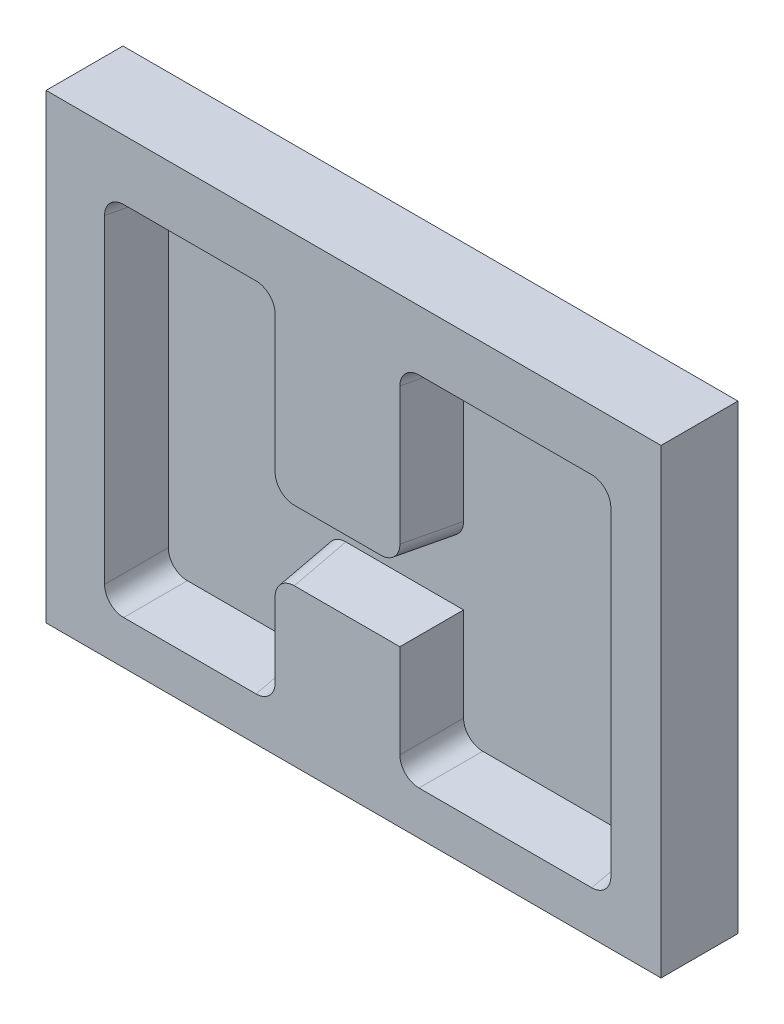
SolidWorks part; units mm, degrees
ref_plane "Front" through (0, 0, 0) normal (0, 0, 1) x (1, 0, 0)
ref_plane "Top" through (0, 0, 0) normal (0, 1, 0) x (1, 0, 0)
ref_plane "Right" through (0, 0, 0) normal (1, 0, 0) x (0, 0, -1)
sketch "Sketch1" plane through (0, 0, 0) normal (0, 0, 1) x (1, 0, 0)
  line L1 (0, 0) -> (203.2, 0)
  line L2 (0, 0) -> (0, 152.4)
  line L3 (0, 152.4) -> (203.2, 152.4)
  line L4 (203.2, 0) -> (203.2, 152.4)
  dimension "D1" = 203.2
  dimension "D2" = 152.4
extrude "Extrude1" add sketch "Sketch1" along normal blind 25.4
sketch "Sketch2" plane through (0, 0, 25.4) normal (0, 0, 1) x (1, 0, 0)
  line L0 (19.3199, 132.5687) -> (75.6886, 132.5687)
  line L1 (75.6886, 132.5687) -> (75.6886, 74.6847)
  line L2 (75.6886, 74.6847) -> (116.9044, 74.6847)
  line L3 (116.9044, 74.6847) -> (116.9044, 132.5687)
  line L4 (116.9044, 132.5687) -> (186.6076, 132.5687)
  line L5 (186.6076, 132.5687) -> (186.6076, 14.3763)
  line L6 (186.6076, 14.3763) -> (116.9044, 14.3763)
  line L7 (116.9044, 14.3763) -> (116.9044, 51.6523)
  line L8 (116.9044, 51.6523) -> (75.6886, 51.6523)
  line L9 (75.6886, 51.6523) -> (75.6886, 14.3763)
  line L10 (75.6886, 14.3763) -> (19.3199, 14.3763)
  line L11 (19.3199, 132.5687) -> (19.3199, 14.3763)
  dimension "D1" = 23.0324
extrude "Cut-Extrude1" cut sketch "Sketch2" against normal blind 19.05 draft 6
fillet "Fillet1" radius 6.35
